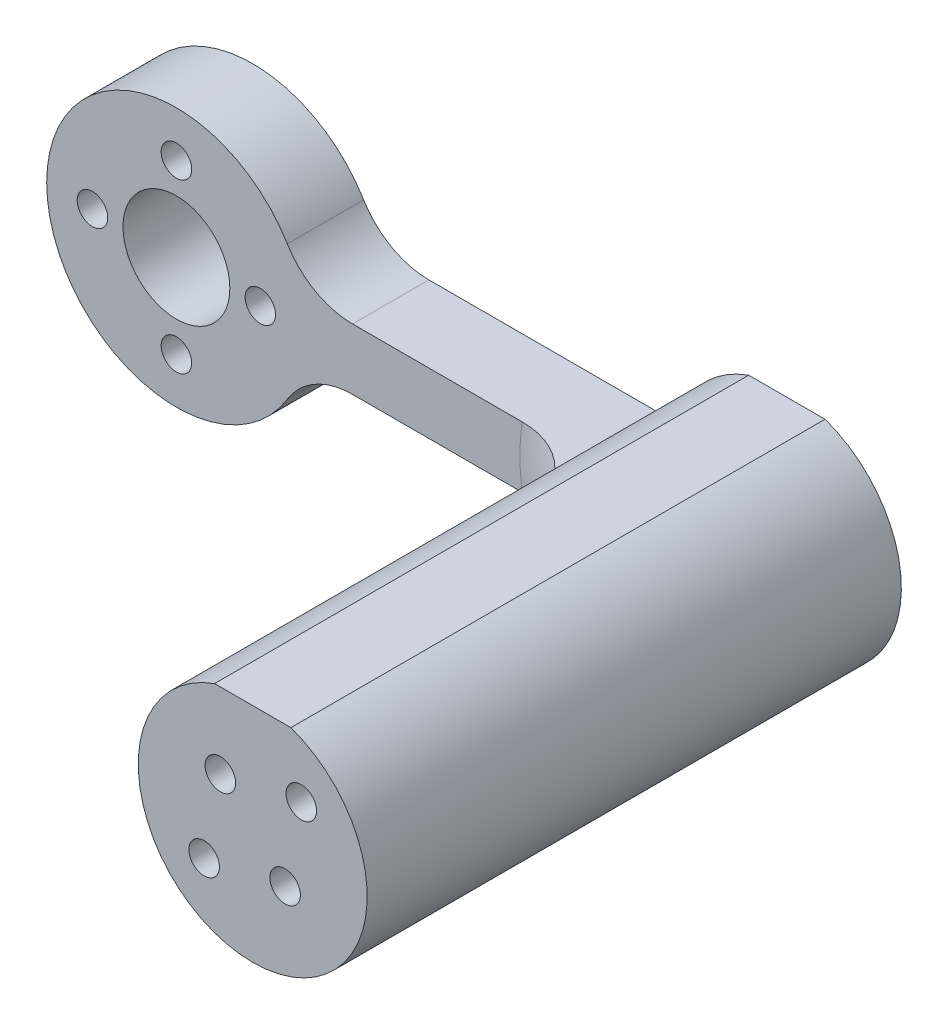
SolidWorks part; units mm, degrees
ref_plane "Front Plane" through (0, 0, 0) normal (0, 0, 1) x (1, 0, 0)
ref_plane "Top Plane" through (0, 0, 0) normal (0, 1, 0) x (1, 0, 0)
ref_plane "Right Plane" through (0, 0, 0) normal (1, 0, 0) x (0, 0, -1)
sketch "Sketch1" plane through (0, 0, 0) normal (0, 0, 1) x (1, 0, 0)
  line L0 (16.5227, 4) -> (55.5432, 4)
  line L1 (16.5227, -4) -> (55.5432, -4)
  line L2 (0, 0) -> (70, 0) construction
  circle A0 centre (0, 0) radius 17
  circle A1 centre (0, 11) radius 2
  circle A2 centre (11, 0) radius 2
  circle A3 centre (0, -11) radius 2
  circle A4 centre (-11, 0) radius 2
  circle A5 centre (70, 0) radius 15
  circle A6 centre (76.364, 6.364) radius 2
  circle A7 centre (74.2426, -4.2426) radius 2
  circle A8 centre (63.636, 6.364) radius 2 construction
  circle A9 centre (74.2426, 4.2426) radius 2 construction
  circle A11 centre (63.636, -6.364) radius 2
  circle A12 centre (76.364, -6.364) radius 2 construction
  circle A13 centre (65.7574, 4.2426) radius 2
  circle A14 centre (65.7574, -4.2426) radius 2 construction
  circle A15 centre (0, 0) radius 7
  point P14 (0, 0)
  point P23 (0, 0)
  point P27 (70, 0)
  point P30 (70, 0)
  point P38 (0, 11)
  point P39 (0, 0)
  point P40 (0, 0)
  point P41 (0, 0)
  point P42 (103.3481, 7.8772)
  point P43 (0, 0)
  point P44 (94.4834, -7.7875)
  point P45 (0, 0)
  point P46 (0, 0)
  point P47 (104.9452, -0.7712)
  point P48 (0, 0)
  point P49 (0, 0)
  point P50 (103.4546, -4)
  point P51 (0, 0)
  point P52 (0, 0)
  dimension "D3" = 4
  dimension "D7" = 4
  dimension "D8" = 4
  dimension "D15" = 14
  dimension "D2" = 11
  dimension "D5" = 9
  dimension "D6" = 6
  dimension "D9" = 70
  dimension "D10" = 6
  dimension "D13" = 8
  dimension "D14" = 6
  dimension "D4" = 4
  dimension "D11" = 4
  dimension "D12" = 4
extrude "Boss-Extrude1" add sketch "Sketch1" along normal blind 10 contours A0 A4 A3 A2 A1 | A5 L0 A0 L1 | A5 A13 A11 A7 A6
sketch "Sketch2" plane through (0, 0, 10) normal (0, 0, 1) x (1, 0, 0)
  circle A1 centre (70, 0) radius 15
  arc A2 (55.5432, -4) -> (55.5432, 4) centre (70, 0) ccw construction
  circle A3 centre (65.7574, 4.2426) radius 2 construction
  circle A4 centre (76.364, 6.364) radius 2 construction
  circle A5 centre (74.2426, -4.2426) radius 2 construction
  circle A6 centre (63.636, -6.364) radius 2 construction
  circle A7 centre (63.636, -6.364) radius 2
  circle A8 centre (74.2426, -4.2426) radius 2
  circle A9 centre (76.364, 6.364) radius 2
  circle A10 centre (65.7574, 4.2426) radius 2
extrude "Boss-Extrude2" add sketch "Sketch2" along normal blind 60
sketch "Sketch3" plane through (0, 0, 70) normal (0, 0, 1) x (1, 0, 0)
  line L0 (65, 14.1421) -> (75, 14.1421)
  circle A0 centre (70, 0) radius 15 construction
  circle A1 centre (70, 0) radius 15
  circle M5 centre (70, 0) radius 15
  dimension "D1" = 10
extrude "Cut-Extrude1" cut sketch "Sketch3" against normal through all contours L0 M5
fillet "Fillet1" radius 10 1 edges at (55, 0, 10)
fillet "Fillet2" radius 10 2 edges at (16.5227, 4, 5) (16.5227, -4, 5)
